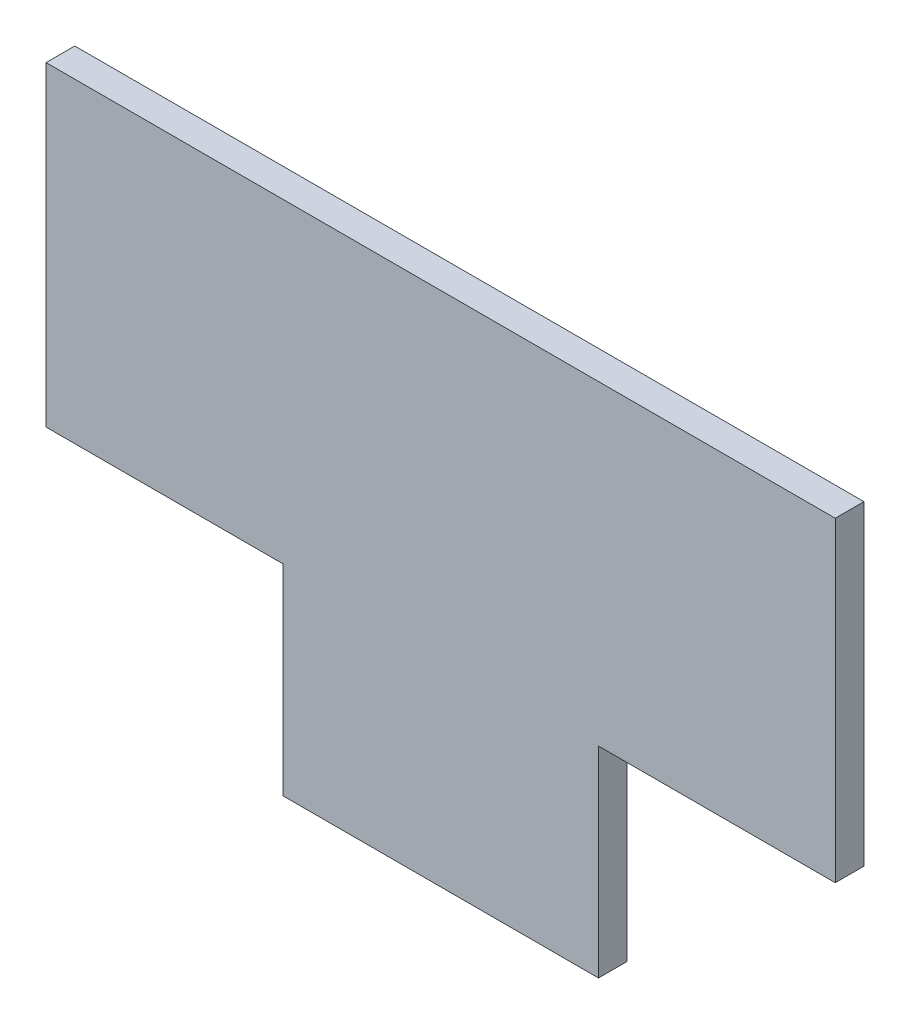
SolidWorks part; units mm, degrees
material "Fibra de vidrio-E"
ref_plane "Alzado" through (0, 0, 0) normal (0, 0, 1) x (1, 0, 0)
ref_plane "Planta" through (0, 0, 0) normal (0, 1, 0) x (1, 0, 0)
ref_plane "Vista lateral" through (0, 0, 0) normal (1, 0, 0) x (0, 0, -1)
sketch "Croquis1" plane through (0, 0, 0) normal (0, 0, 1) x (1, 0, 0)
  line L0 (-5.5, 0) -> (5.5, 0)
  line L1 (5.5, 0) -> (5.5, 7)
  line L2 (5.5, 7) -> (13.75, 7)
  line L3 (13.75, 7) -> (13.75, 18)
  line L4 (13.75, 18) -> (-13.75, 18)
  line L5 (-13.75, 18) -> (-13.75, 7)
  line L6 (-13.75, 7) -> (-5.5, 7)
  line L7 (-5.5, 7) -> (-5.5, 0)
  point P11 (0, 18)
  point P12 (0, 0)
  dimension "D1" = 11
  dimension "D2" = 27.5
  dimension "D3" = 8.25
  dimension "D4" = 7
extrude "Saliente-Extruir1" add sketch "Croquis1" along normal blind 1
